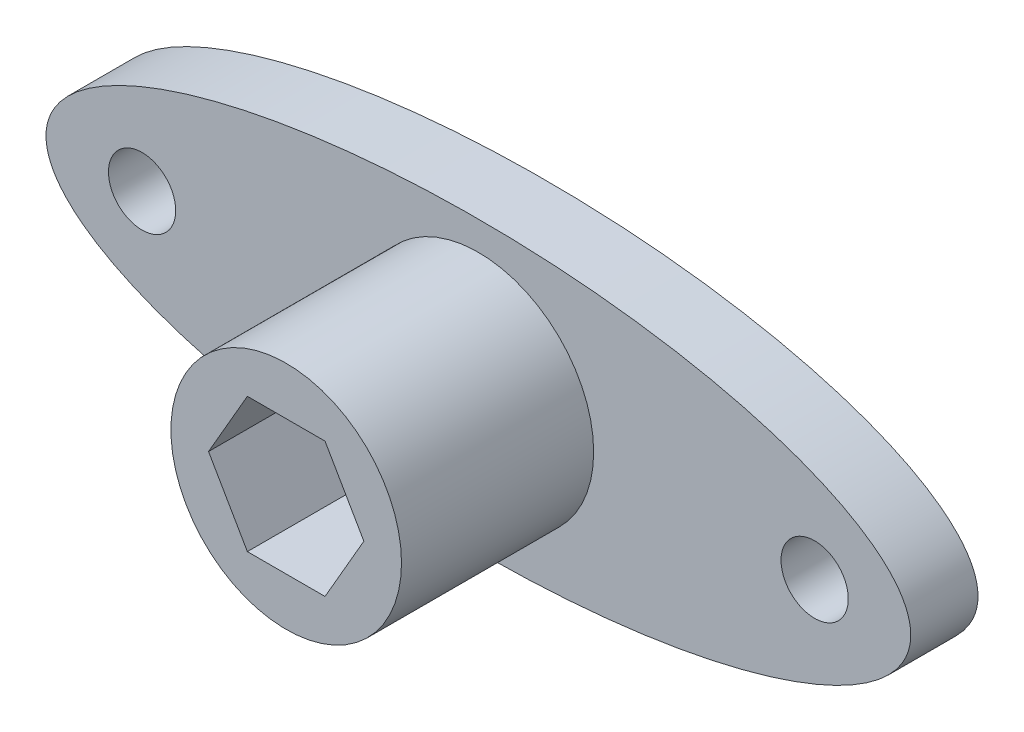
SolidWorks part; units mm, degrees
material "Plain Carbon Steel"
ref_plane "Front Plane" through (0, 0, 0) normal (0, 0, 1) x (1, 0, 0)
ref_plane "Top Plane" through (0, 0, 0) normal (0, 1, 0) x (1, 0, 0)
ref_plane "Right Plane" through (0, 0, 0) normal (1, 0, 0) x (0, 0, -1)
sketch "Sketch2" plane through (0, 0, 0) normal (0, 0, 1) x (1, 0, 0)
  line L0 (0, 7.5) -> (0, -7.5) construction
  circle A0 centre (-17.5, 0) radius 1.75
  circle A1 centre (17.5, 0) radius 1.75
  ellipse E0 centre (0, 0) end of major axis (22.5, 0) minor radius 7.5
  dimension "D4" = 3.5
  dimension "D1" = 45
  dimension "D2" = 15
  dimension "D3" = 5
extrude "Boss-Extrude1" add sketch "Sketch2" along normal blind 3.5
sketch "Sketch3" plane through (0, 0, 3.5) normal (0, 0, 1) x (1, 0, 0)
  circle A0 centre (0, 0) radius 6
  dimension "D1" = 12
extrude "Boss-Extrude3" add sketch "Sketch3" along normal blind 10 contours A0
sketch "Sketch4" plane through (0, 0, 13.5) normal (0, 0, 1) x (1, 0, 0)
  line L1 (2.0207, -3.5) -> (4.0415, 0)
  line L2 (4.0415, 0) -> (2.0207, 3.5)
  line L3 (2.0207, 3.5) -> (-2.0207, 3.5)
  line L4 (-2.0207, 3.5) -> (-4.0415, 0)
  line L5 (-4.0415, 0) -> (-2.0207, -3.5)
  line L6 (-2.0207, -3.5) -> (2.0207, -3.5)
  circle A0 centre (0, 0) radius 3.5 construction
  dimension "D2" = 7
  dimension "D1" = 7
extrude "Cut-Extrude1" cut sketch "Sketch4" against normal blind 6.5 contours L1 L2 L3 L4 L5 L6
